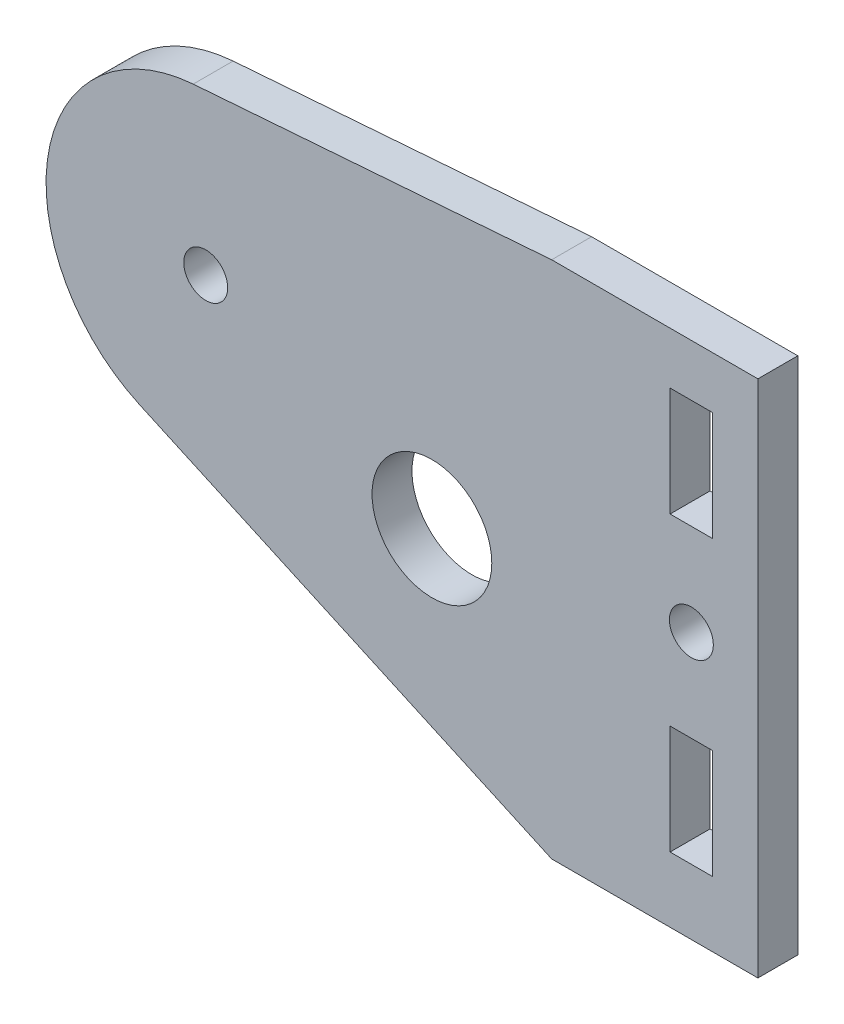
SolidWorks part; units mm, degrees
ref_plane "Спереди" through (0, 0, 0) normal (0, 0, 1) x (1, 0, 0)
ref_plane "Сверху" through (0, 0, 0) normal (0, 1, 0) x (1, 0, 0)
ref_plane "Справа" through (0, 0, 0) normal (1, 0, 0) x (0, 0, -1)
other "Configuration Table"
sketch "Eskiz_kontur" plane through (0, 0, 0) normal (0, 0, 1) x (1, 0, 0)
  line L0 (41.5, -25) -> (26, -25)
  line L1 (26, -25) -> (-4.9763, -10.9195)
  line L2 (41.5, 14) -> (41.5, -25)
  line L3 (26, 14) -> (41.5, 14)
  line L4 (-0.9415, 11.963) -> (26, 14)
  line L5 (38.1, -20.1) -> (38.1, -11.9)
  line L6 (38.1, -11.9) -> (34.9, -11.9)
  line L7 (34.9, -20.1) -> (38.1, -20.1)
  line L8 (34.9, -11.9) -> (34.9, -20.1)
  line L9 (38.1, 1.9) -> (38.1, 10.1)
  line L10 (38.1, 10.1) -> (34.9, 10.1)
  line L11 (34.9, 1.9) -> (38.1, 1.9)
  line L12 (34.9, 10.1) -> (34.9, 1.9)
  arc A0 (-4.9763, -10.9195) -> (-0.9415, 11.963) centre (0, 0) cw
extrude "Plastina" add sketch "Eskiz_kontur" along normal blind 3
sketch "Eskiz_otverstiya" plane through (0, 0, 0) normal (0, 0, 1) x (1, 0, 0)
  circle A0 centre (17, -8) radius 4.5
  circle A1 centre (0, 0) radius 1.65
  circle A2 centre (36.5, -5) radius 1.65
  dimension "d1" = 9
  dimension "d2" = 3.3
  dimension "d3" = 3.3
extrude "Otverstiya" cut sketch "Eskiz_otverstiya" against normal through all and the other way through all
equation "\"T3\" = 3"
equation "\"T5\" = 5"
equation "\"D_M3\" = 3.3"
equation "\"D_M2\" = 2.2"
equation "\"D_M3_TAP\" = 2.5"
equation "\"D_M4\" = 4.5"
equation "\"L1\" = 100"
equation "\"L2\" = 100"
equation "\"D1@Plastina\" = \"T3\""
equation "\"d2@Eskiz_otverstiya\" = \"D_M3\""
equation "\"d3@Eskiz_otverstiya\" = \"D_M3\""
